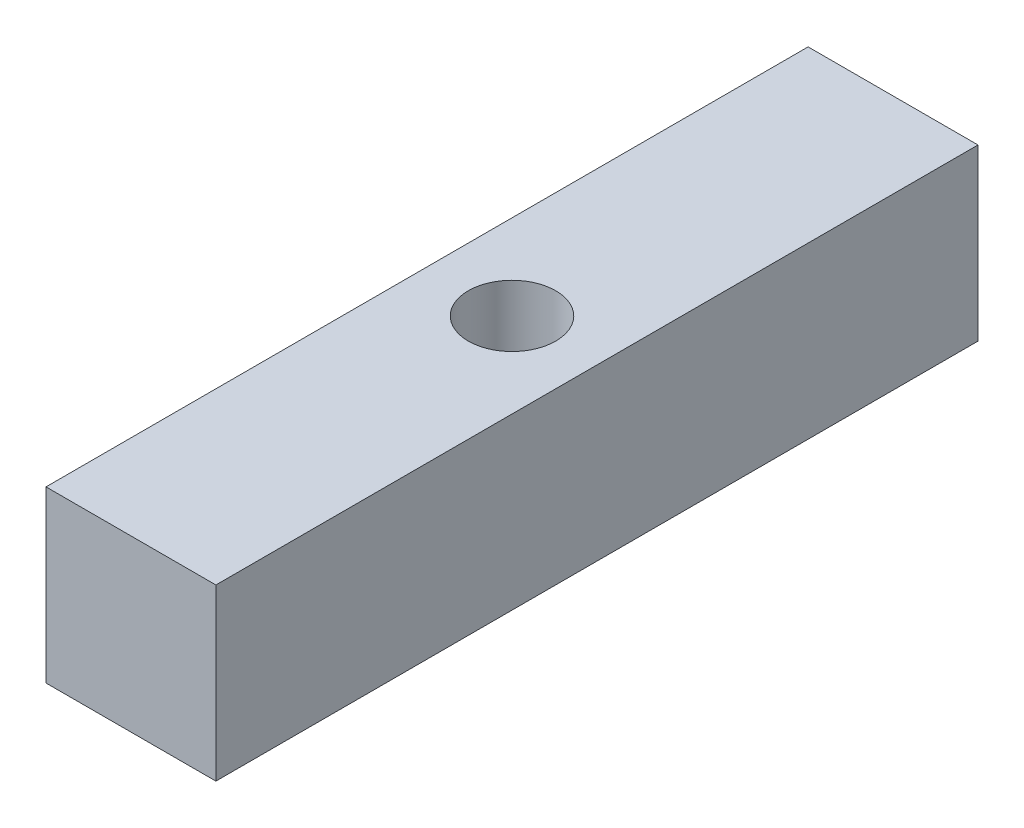
SolidWorks part; units mm, degrees
ref_plane "Front Plane" through (0, 0, 0) normal (0, 0, 1) x (1, 0, 0)
ref_plane "Top Plane" through (0, 0, 0) normal (0, 1, 0) x (1, 0, 0)
ref_plane "Right Plane" through (0, 0, 0) normal (1, 0, 0) x (0, 0, -1)
sketch "Sketch1" plane through (0, 0, 0) normal (0, 1, 0) x (1, 0, 0)
  line L1 (-4.445, 19.939) -> (4.445, 19.939)
  line L2 (-4.445, 19.939) -> (-4.445, -19.939)
  line L3 (-4.445, -19.939) -> (4.445, -19.939)
  line L4 (4.445, 19.939) -> (4.445, -19.939)
  circle A0 centre (0, 0) radius 2.286
  point P4 (0, -19.939)
  point P6 (-4.445, 0)
  dimension "D3" = 4.572
  dimension "D1" = 8.89
  dimension "D2" = 39.878
extrude "Boss-Extrude1" add sketch "Sketch1" along normal blind 8.89
